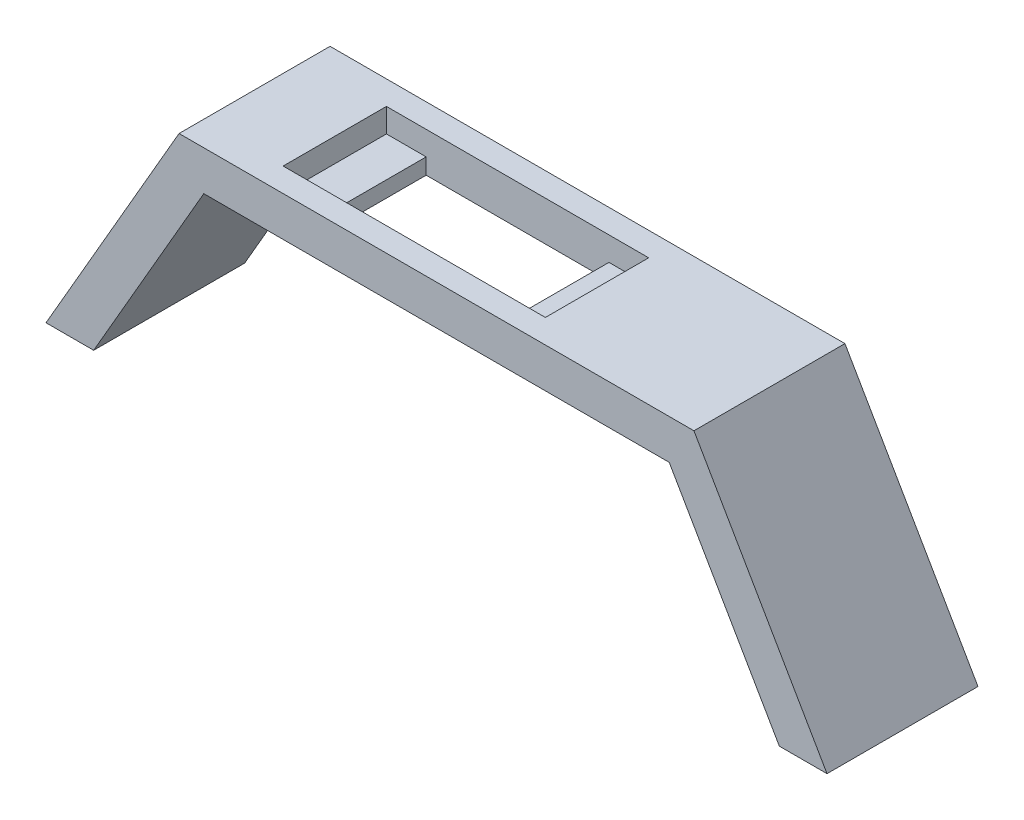
SolidWorks part; units mm, degrees
ref_plane "Front Plane" through (0, 0, 0) normal (0, 0, 1) x (1, 0, 0)
ref_plane "Top Plane" through (0, 0, 0) normal (0, 1, 0) x (1, 0, 0)
ref_plane "Right Plane" through (0, 0, 0) normal (1, 0, 0) x (0, 0, -1)
sketch "Sketch1" plane through (0, 0, 0) normal (0, 0, 1) x (1, 0, 0)
  line L0 (-29.2836, 0) -> (29.2836, 0)
  line L1 (29.2836, 0) -> (43.14, -24)
  line L2 (43.14, -24) -> (49.14, -24)
  line L3 (49.14, -24) -> (32.3968, 5)
  line L4 (32.3968, 5) -> (-32.3968, 5)
  line L5 (-32.3968, 5) -> (-49.14, -24)
  line L6 (-49.14, -24) -> (-43.14, -24)
  line L7 (-43.14, -24) -> (-29.2836, 0)
  point P6 (0, 0)
  dimension "D1" = 5
  dimension "D2" = 120
  dimension "D3" = 24
  dimension "D4" = 98.28
  dimension "D5" = 6
extrude "Boss-Extrude1" add sketch "Sketch1" along normal blind 19
sketch "Sketch2" plane through (0, 5, 0) normal (0, 1, 0) x (1, 0, 0)
  line L1 (10.7, -3) -> (-22.3, -3)
  line L2 (10.7, -3) -> (10.7, -16)
  line L3 (10.7, -16) -> (-22.3, -16)
  line L4 (-22.3, -3) -> (-22.3, -16)
  line L5 (10.7, -3) -> (-22.3, -16) construction
  line L6 (10.7, -16) -> (-22.3, -3) construction
  line L7 (32.3968, 0) -> (-32.3968, 0) construction
  point P0 (-5.8, -9.5)
  dimension "D1" = 33
  dimension "D2" = 13
  dimension "D3" = 10.7
  dimension "D4" = 3
extrude "Cut-Extrude1" cut sketch "Sketch2" against normal blind 3
sketch "Sketch3" plane through (0, 2, 0) normal (0, 1, 0) x (1, 0, 0)
  line L0 (-22.3, -16) -> (10.7, -16) construction
  line L1 (-17.3, -3) -> (5.7, -3)
  line L2 (-17.3, -3) -> (-17.3, -16)
  line L3 (-17.3, -16) -> (5.7, -16)
  line L4 (5.7, -3) -> (5.7, -16)
  line L5 (-17.3, -3) -> (5.7, -16) construction
  line L6 (-17.3, -16) -> (5.7, -3) construction
  line L7 (10.7, -3) -> (-22.3, -3) construction
  line L9 (10.7, -16) -> (10.7, -3) construction
  line L10 (-22.3, -3) -> (-22.3, -16) construction
  point P0 (-5.8, -9.5)
  dimension "D1" = 5
  dimension "D2" = 5
extrude "Cut-Extrude2" cut sketch "Sketch3" against normal up to next
